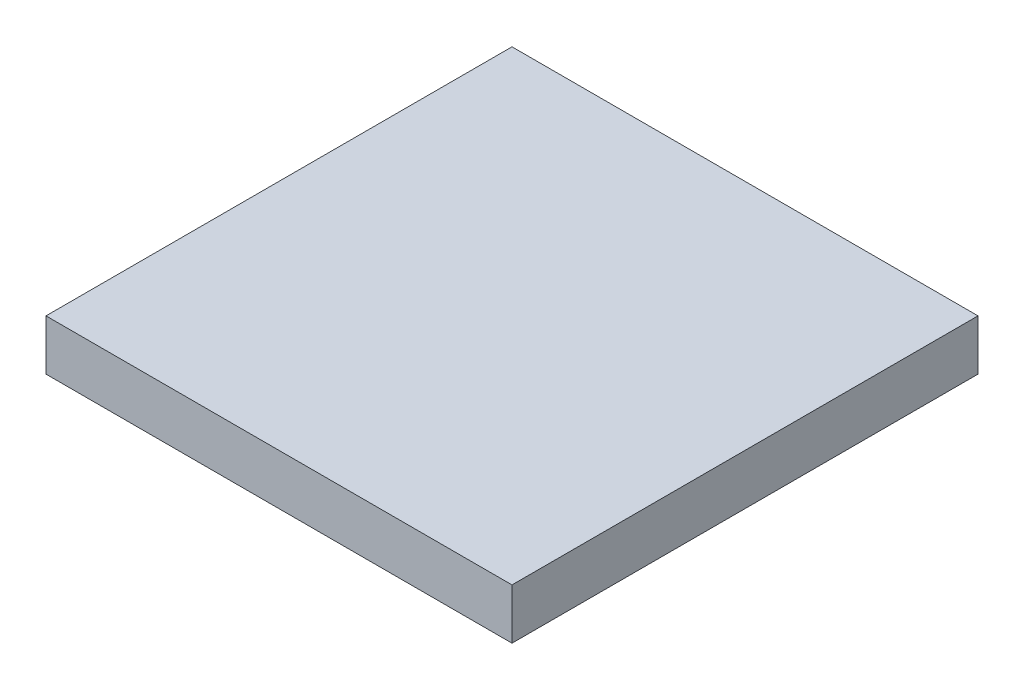
SolidWorks part; units mm, degrees
ref_plane "Front Plane" through (0, 0, 0) normal (0, 0, 1) x (1, 0, 0)
ref_plane "Top Plane" through (0, 0, 0) normal (0, 1, 0) x (1, 0, 0)
ref_plane "Right Plane" through (0, 0, 0) normal (1, 0, 0) x (0, 0, -1)
other "Configuration Table"
sketch "Sketch1" plane through (0, 0, 0) normal (0, 0, 1) x (1, 0, 0)
  line L1 (0, -25) -> (60, -25)
  line L2 (0, -25) -> (0, -18.5)
  line L3 (0, -18.5) -> (60, -18.5)
  line L4 (60, -25) -> (60, -18.5)
extrude "MTG_montaj_braketi_3mm_1" add sketch "Sketch1" against normal blind 60 from offset 30 separate body
